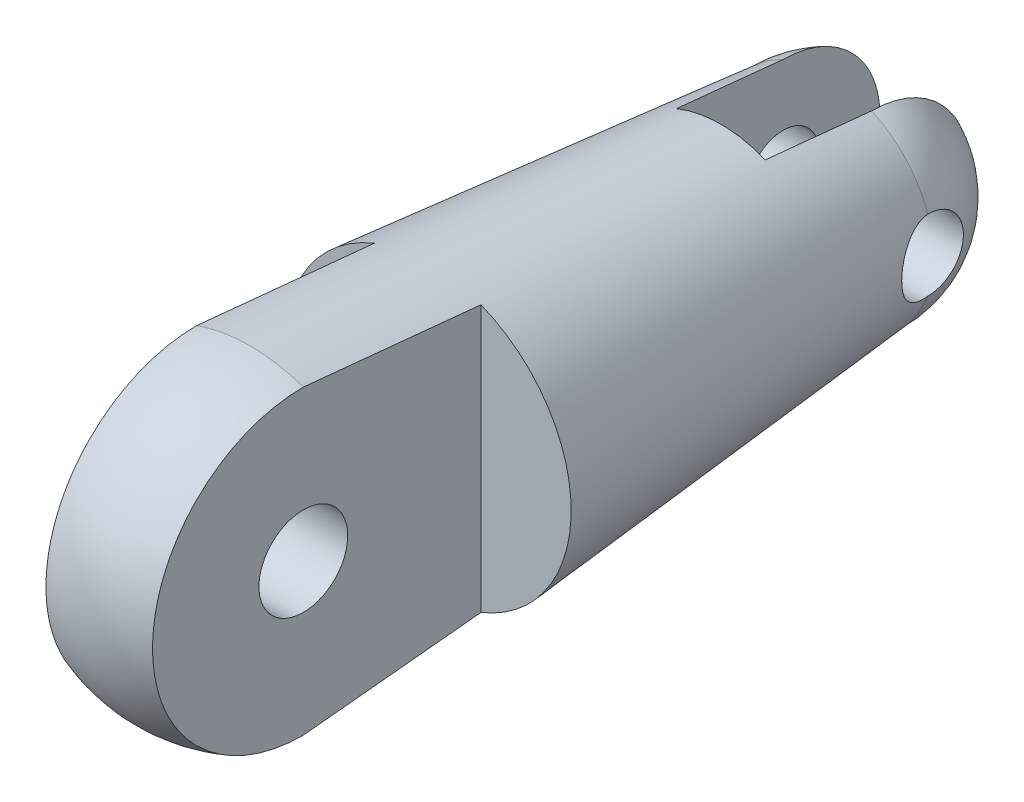
SolidWorks part; units mm, degrees
ref_plane "Ön Düzlem" through (0, 0, 0) normal (0, 0, 1) x (1, 0, 0)
ref_plane "Üst Düzlem" through (0, 0, 0) normal (0, 1, 0) x (1, 0, 0)
ref_plane "Sağ Düzlem" through (0, 0, 0) normal (1, 0, 0) x (0, 0, -1)
sketch "Sketch1" plane through (0, 0, 0) normal (1, 0, 0) x (0, 0, -1)
  line L0 (-18, 0) -> (77, 0)
  line L1 (0, 18) -> (65, 12)
  line L3 (-43.473, 0) -> (160.3225, 0) construction
  arc A0 (77, 0) -> (65, 12) centre (65, 0) ccw
  arc A1 (0, 18) -> (-18, 0) centre (0, 0) ccw
  dimension "D1" = 18
  dimension "D2" = 12
revolve "Revolve1" add sketch "Sketch1" angle 360 about L3
sketch "Sketch2" plane through (0, 0, 0) normal (1, 0, 0) x (0, 0, -1)
  line L0 (65, 12) -> (65, -12) construction
  circle A0 centre (0, 0) radius 5
  circle A1 centre (65, 0) radius 4
extrude "Cut-Extrude1" cut sketch "Sketch2" against normal mid plane 60
sketch "Sketch3" plane through (0, 0, 0) normal (0, 1, 0) x (1, 0, 0)
  line L1 (-26.3303, 20) -> (-6, 20)
  line L2 (-26.3303, 20) -> (-26.3303, -21.442)
  line L3 (-26.3303, -21.442) -> (-6, -21.442)
  line L4 (-6, 20) -> (-6, -21.442)
  line L5 (22.2001, 20) -> (6, 20)
  line L6 (22.2001, 20) -> (22.2001, -24.8188)
  line L7 (22.2001, -24.8188) -> (6, -24.8188)
  line L8 (6, 20) -> (6, -24.8188)
  dimension "D1" = 6
  dimension "D2" = 6
  dimension "D3" = 20
  dimension "D4" = 20
extrude "Cut-Extrude2" cut sketch "Sketch3" against normal mid plane 40
sketch "Sketch4" plane through (0, 0, 0) normal (0, 1, 0) x (1, 0, 0)
  line L0 (11.3137, 65) -> (-11.3137, 65) construction
  line L1 (-5, 77) -> (5, 77)
  line L2 (-5, 77) -> (-5, 53)
  line L3 (-5, 53) -> (5, 53)
  line L4 (5, 77) -> (5, 53)
  line L5 (-5, 77) -> (5, 53) construction
  line L6 (-5, 53) -> (5, 77) construction
  point P0 (0, 65)
  dimension "D1" = 10
  dimension "D2" = 12
extrude "Cut-Extrude3" cut sketch "Sketch4" against normal mid plane 40
